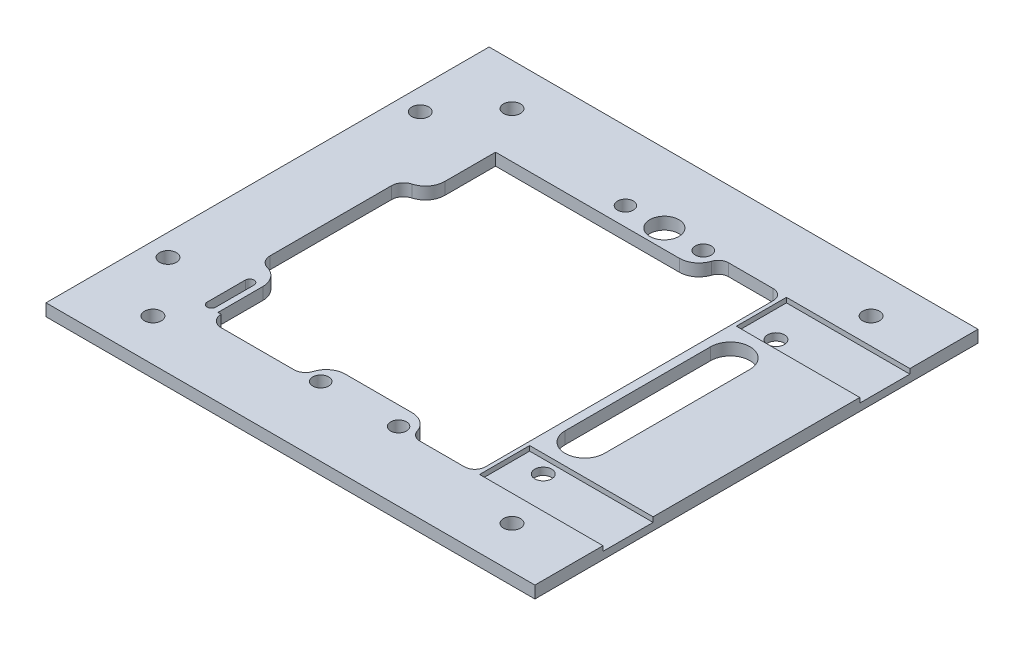
SolidWorks part; units mm, degrees
ref_plane "Front" through (0, 0, 0) normal (0, 0, 1) x (1, 0, 0)
ref_plane "Top" through (0, 0, 0) normal (0, 1, 0) x (1, 0, 0)
ref_plane "Right" through (0, 0, 0) normal (1, 0, 0) x (0, 0, -1)
sketch "Sketch1" plane through (0, 0, 0) normal (0, 1, 0) x (1, 0, 0)
  line L1 (-31.9913, 28.9941) -> (31.9913, 28.9941)
  line L2 (-31.9913, 28.9941) -> (-31.9913, -28.9941)
  line L3 (-31.9913, -28.9941) -> (31.9913, -28.9941)
  line L4 (31.9913, 28.9941) -> (31.9913, -28.9941)
  line L5 (-31.9913, 28.9941) -> (31.9913, -28.9941) construction
  line L6 (-31.9913, -28.9941) -> (31.9913, 28.9941) construction
  point P0 (0, 0)
  dimension "D1" = 57.9882
  dimension "D2" = 63.9826
extrude "Boss-Extrude1" add sketch "Sketch1" along normal blind 1.5875
sketch "Sketch2" plane through (0, 1.5875, 0) normal (0, 1, 0) x (1, 0, 0)
  line L7 (-23.495, -23.495) -> (23.495, -23.495)
  line L8 (-23.495, -23.495) -> (-23.495, 23.495)
  line L9 (-23.495, 23.495) -> (23.495, 23.495)
  line L10 (23.495, -23.495) -> (23.495, 23.495)
  line L11 (-23.495, -23.495) -> (23.495, 23.495) construction
  line L12 (-23.495, 23.495) -> (23.495, -23.495) construction
  line L13 (-5.0927, 19.939) -> (5.0927, 19.939)
  line L14 (-5.0927, 19.939) -> (-5.0927, -19.939)
  line L15 (-5.0927, -19.939) -> (5.0927, -19.939)
  line L16 (5.0927, 19.939) -> (5.0927, -19.939)
  line L17 (-5.0927, 19.939) -> (5.0927, -19.939) construction
  line L18 (-5.0927, -19.939) -> (5.0927, 19.939) construction
  circle A0 centre (0, 0) radius 0.514
  circle A1 centre (-23.495, -23.495) radius 1.1049
  circle A2 centre (23.495, -23.495) radius 1.1049
  circle A3 centre (-23.495, 23.495) radius 1.1049
  circle A4 centre (23.495, 23.495) radius 1.1049
  circle A5 centre (-5.0927, 19.939) radius 1.0414
  circle A6 centre (5.0927, 19.939) radius 1.0414
  circle A7 centre (5.0927, -19.939) radius 1.0414
  circle A8 centre (-5.0927, -19.939) radius 1.0414
  circle A9 centre (0, 0) radius 0.2908
  point P0 (0, 0)
  point P18 (0, 0)
  dimension "D6" = 2.0828
  dimension "D7" = 2.0828
  dimension "D8" = 2.0828
  dimension "D9" = 2.0828
  dimension "D2" = 46.99
  dimension "D3" = 46.99
  dimension "D4" = 46.99
  dimension "D5" = 10.1854
extrude "Cut-Extrude1" cut sketch "Sketch2" against normal blind 7.62 contours A1 | A2 | A4 | A3 | A0 | A8 | A7 | A5 | A6
sketch "Sketch3" plane through (0, 1.5875, 0) normal (0, 1, 0) x (1, 0, 0)
  line L0 (0, 0) -> (19.05, 0)
  line L1 (19.05, -9.525) -> (19.05, 9.525) construction
  line L2 (0, 0) -> (13.9246, 0)
  line L7 (5.0927, 19.939) -> (-5.0927, 19.939)
  line L16 (-20.955, -13.375) -> (-20.955, -18.375)
  line L17 (16.4799, -9.525) -> (16.4799, 9.525)
  line L18 (21.6201, -9.525) -> (21.6201, 9.525)
  line L21 (-20.955, -13.375) -> (-20.955, -18.375) construction
  line L22 (-20.3835, -13.375) -> (-20.3835, -18.375)
  line L23 (-21.5265, -13.375) -> (-21.5265, -18.375)
  line L24 (19.05, 0) -> (19.05, 9.525)
  circle A0 centre (0, 19.939) radius 1.905
  circle A1 centre (19.05, 9.525) radius 2.54
  circle A2 centre (19.05, -9.525) radius 2.54
  circle A4 centre (-23.495, -23.495) radius 1.1049 construction
  arc A15 (-20.3835, -13.375) -> (-21.5265, -13.375) centre (-20.955, -13.375) ccw
  arc A16 (-21.5265, -18.375) -> (-20.3835, -18.375) centre (-20.955, -18.375) ccw
  arc A17 (16.4799, -9.525) -> (21.6201, -9.525) centre (19.05, -9.525) ccw
  arc A18 (21.6201, 9.525) -> (16.4799, 9.525) centre (19.05, 9.525) ccw
  point P3 (19.05, 0)
  point P23 (-20.955, -15.875)
  dimension "D7" = 3.81
  dimension "D1" = 5.08
  dimension "D4" = 1.143
  dimension "D6" = 7.62
  dimension "D2" = 19.05
  dimension "D3" = 9.525
  dimension "D5" = 2.54
  dimension "D8" = 5
extrude "Cut-Extrude2" cut sketch "Sketch3" against normal through all
sketch "Sketch4" plane through (0, 1.5875, 0) normal (0, 1, 0) x (1, 0, 0)
  line L0 (0, 0) -> (33.6169, 0)
  line L1 (33.6169, 0) -> (33.6169, -13.5255)
  line L2 (-31.9913, -28.9941) -> (31.9913, -28.9941) construction
  line L3 (33.6169, -13.5255) -> (15.8369, -13.5255)
  line L4 (33.6169, -13.5255) -> (33.6169, -20.0787)
  line L5 (33.6169, -20.0787) -> (15.8369, -20.0787)
  line L6 (15.8369, -13.5255) -> (15.8369, -20.0787)
  line L7 (33.6169, 20.0787) -> (15.8369, 20.0787)
  line L8 (15.8369, 13.5255) -> (15.8369, 20.0787)
  line L9 (33.6169, 13.5255) -> (15.8369, 13.5255)
  line L10 (33.6169, 13.5255) -> (33.6169, 20.0787)
  line L12 (31.9913, -28.9941) -> (31.9913, 28.9941) construction
  dimension "D1" = 15.4686
  dimension "D2" = 16.1544
  dimension "D3" = 6.5532
  dimension "D4" = 17.78
extrude "Cut-Extrude3" cut sketch "Sketch4" against normal blind 0.635
sketch "Sketch5" plane through (0, 1.5875, 0) normal (0, 1, 0) x (1, 0, 0)
  line L0 (-31.9913, 0) -> (-2.1463, 0)
  line L9 (-31.9913, 28.9941) -> (-31.9913, -28.9941) construction
  line L11 (-19.6469, -17.4943) -> (15.3543, -17.4943)
  line L12 (-19.6469, -17.4943) -> (-19.6469, 17.4942)
  line L13 (-19.6469, 17.4942) -> (15.3543, 17.4942)
  line L14 (15.3543, -17.4943) -> (15.3543, 17.4942)
  line L15 (-19.6469, -17.4943) -> (15.3543, 17.4942) construction
  line L16 (-19.6469, 17.4942) -> (15.3543, -17.4943) construction
  dimension "D1" = 35.0012
  dimension "D2" = 34.9885
  dimension "D3" = 29.845
extrude "Cut-Extrude4" cut sketch "Sketch5" against normal through all
sketch "Sketch6" plane through (0, 1.5875, 0) normal (0, 1, 0) x (1, 0, 0)
  line L0 (-21.0693, -8.9916) -> (-21.0693, 6.8834) construction
  line L1 (-22.6568, -8.9916) -> (-22.6568, 6.8834)
  line L2 (-19.4818, -8.9916) -> (-19.4818, 6.8834)
  line L3 (-17.7038, -18.8341) -> (-8.1788, -18.8341) construction
  line L4 (-17.7038, -17.3101) -> (-8.1788, -17.3101)
  line L5 (-17.7038, -20.3581) -> (-8.1788, -20.3581)
  line L6 (-31.9913, -28.9941) -> (31.9913, -28.9941) construction
  line L7 (-31.9913, 28.9941) -> (-31.9913, -28.9941) construction
  line L8 (-19.6469, -17.4943) -> (-19.6469, -18.8341)
  line L9 (-19.2278, -18.8341) -> (-19.6469, -18.8341)
  line L10 (-17.7038, -17.3101) -> (-19.6469, -17.4943)
  line L11 (13.9844, -18.8341) -> (8.1427, -18.8341) construction
  line L12 (13.9844, -20.204) -> (8.1427, -20.204)
  line L13 (13.9844, -17.4642) -> (8.1427, -17.4642)
  line L15 (15.3543, -18.8341) -> (15.3543, -17.4943)
  line L16 (15.3543, -17.4943) -> (14.9043, -17.4943)
  line L17 (-19.6469, -17.4943) -> (15.3543, -17.4943) construction
  line L18 (14.9043, -17.4943) -> (14.2268, -17.4858)
  line L19 (0, 0) -> (11.7733, 0)
  line L20 (14.9043, 17.4943) -> (14.2268, 17.4858)
  line L21 (15.3543, 17.4943) -> (14.9043, 17.4943)
  line L22 (15.3543, 18.8341) -> (15.3543, 17.4943)
  line L23 (13.9844, 18.8341) -> (8.1427, 18.8341) construction
  line L24 (13.9844, 20.204) -> (8.1427, 20.204)
  line L25 (13.9844, 17.4642) -> (8.1427, 17.4642)
  arc A0 (-22.6568, -8.9916) -> (-19.4818, -8.9916) centre (-21.0693, -8.9916) ccw
  arc A1 (-19.4818, 6.8834) -> (-22.6568, 6.8834) centre (-21.0693, 6.8834) ccw
  arc A2 (-17.7038, -17.3101) -> (-17.7038, -20.3581) centre (-17.7038, -18.8341) ccw
  arc A3 (-8.1788, -20.3581) -> (-8.1788, -17.3101) centre (-8.1788, -18.8341) ccw
  arc A4 (13.9844, -20.204) -> (13.9844, -17.4642) centre (13.9844, -18.8341) ccw
  arc A5 (8.1427, -17.4642) -> (8.1427, -20.204) centre (8.1427, -18.8341) ccw
  arc A6 (13.9844, 20.204) -> (13.9844, 17.4642) centre (13.9844, 18.8341) cw
  arc A7 (8.1427, 17.4642) -> (8.1427, 20.204) centre (8.1427, 18.8341) cw
  point P2 (-21.0693, -1.0541)
  point P8 (-12.9413, -18.8341)
  point P25 (11.0635, -18.8341)
  point P46 (11.0635, 18.8341)
  line M6 (15.3543, -17.4943) -> (-19.6469, -17.4943)
  line M7 (-19.6469, -17.4943) -> (-19.6469, 17.4942)
  line M8 (-19.6469, 17.4942) -> (15.3543, 17.4942)
  dimension "D3" = 1.524
  dimension "D1" = 3.175
  dimension "D2" = 15.875
  dimension "D4" = 9.525
  dimension "D5" = 10.16
  dimension "D6" = 19.05
  dimension "D7" = 10.922
  dimension "D8" = 27.94
  dimension "D9" = 90
extrude "Cut-Extrude5" cut sketch "Sketch6" against normal through all contours L5 A3 A2 M6 | A2 L8 L9 M6 | A1 L1 A0 M7 | A5 L12 A4 M6 | A4 L15 M6 | A7 A6 L24 M8 | L22 A6 M8
sketch "Sketch7" plane through (0, 1.5875, 0) normal (0, 1, 0) x (1, 0, 0)
  line L0 (-21.5265, -15.875) -> (-29.1465, -15.875)
  line L3 (-21.5265, -13.375) -> (-21.5265, -18.375) construction
  line L4 (-29.1465, -15.875) -> (-29.1465, 17.145)
  circle A4 centre (-29.1465, -15.875) radius 1.1049
  circle A5 centre (-29.1465, 17.145) radius 1.1049
  dimension "D1" = 2.2098
  dimension "D2" = 2.2098
  dimension "D3" = 33.02
  dimension "D4" = 7.62
extrude "Cut-Extrude6" cut sketch "Sketch7" against normal through all contours A4 | A5
fillet "Fillet1" radius 2.54 2 edges at (-19.6469, 0.7937, 9.6965) (-19.6469, 0.7937, -7.5883)
fillet "Fillet2" radius 2.54 1 edges at (-7.4526, 0.7937, 17.4943)
fillet "Fillet5" radius 2.54 1 edges at (7.8572, 0.7937, 17.4943)
fillet "Fillet6" radius 2.54 1 edges at (7.8572, 0.7937, -17.4942)
sketch "Sketch8" plane through (0, 0.9525, 0) normal (0, 1, 0) x (1, 0, 0)
  line L0 (19.3167, -20.0787) -> (19.3167, 20.0787)
  line L1 (31.9913, -20.0787) -> (15.8369, -20.0787) construction
  line L2 (31.9913, 20.0787) -> (15.8369, 20.0787) construction
  line L3 (15.8369, 13.5255) -> (15.8369, 20.0787) construction
  line L4 (31.9913, 13.5255) -> (15.8369, 13.5255) construction
  line L5 (31.9913, -13.5255) -> (15.8369, -13.5255) construction
  circle A0 centre (19.3167, 15.2273) radius 1.1049
  circle A1 centre (19.3167, -15.2273) radius 1.1049
  dimension "D4" = 2.2098
  dimension "D5" = 2.2098
  dimension "D1" = 3.4798
  dimension "D2" = 1.7018
  dimension "D3" = 1.7018
extrude "Cut-Extrude7" cut sketch "Sketch8" against normal blind 2.54 contours A1 | A0
